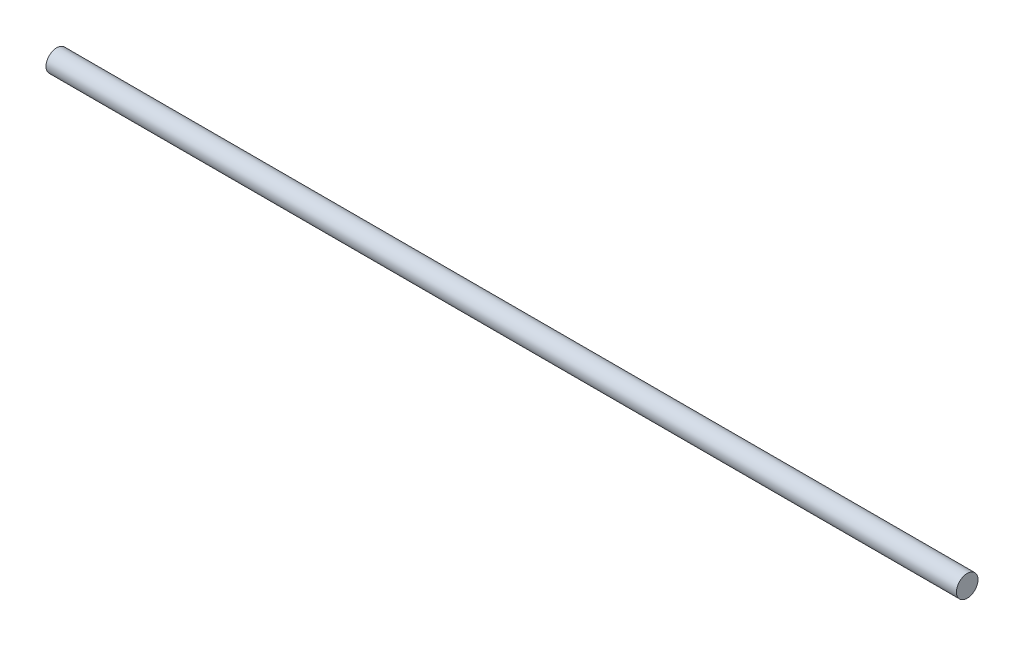
SolidWorks part; units mm, degrees
ref_plane "Front Plane" through (0, 0, 0) normal (0, 0, 1) x (1, 0, 0)
ref_plane "Top Plane" through (0, 0, 0) normal (0, 1, 0) x (1, 0, 0)
ref_plane "Right Plane" through (0, 0, 0) normal (1, 0, 0) x (0, 0, -1)
sketch "Sketch1" plane through (0, 0, 0) normal (0, 0, 1) x (1, 0, 0)
  line L0 (0, 0) -> (130391.3026, 0) construction
  line L1 (0, 0) -> (0, -130391.3026) construction
  line L2 (-268, 6.35) -> (268, 6.35)
  line L3 (-268, 6.35) -> (-268, 0)
  line L4 (268, 6.35) -> (268, 0)
  line L5 (268, 0) -> (-268, 0)
  dimension "D1" = 536
  dimension "D2" = 12.7
revolve "Revolve1" add sketch "Sketch1" angle 360 about L0
cosmetic thread "Cosmetic Thread1" parameters "D1"=44.5, "D2"=11.1887
cosmetic thread "Cosmetic Thread2" parameters "D1"=44.5, "D2"=11.1887
